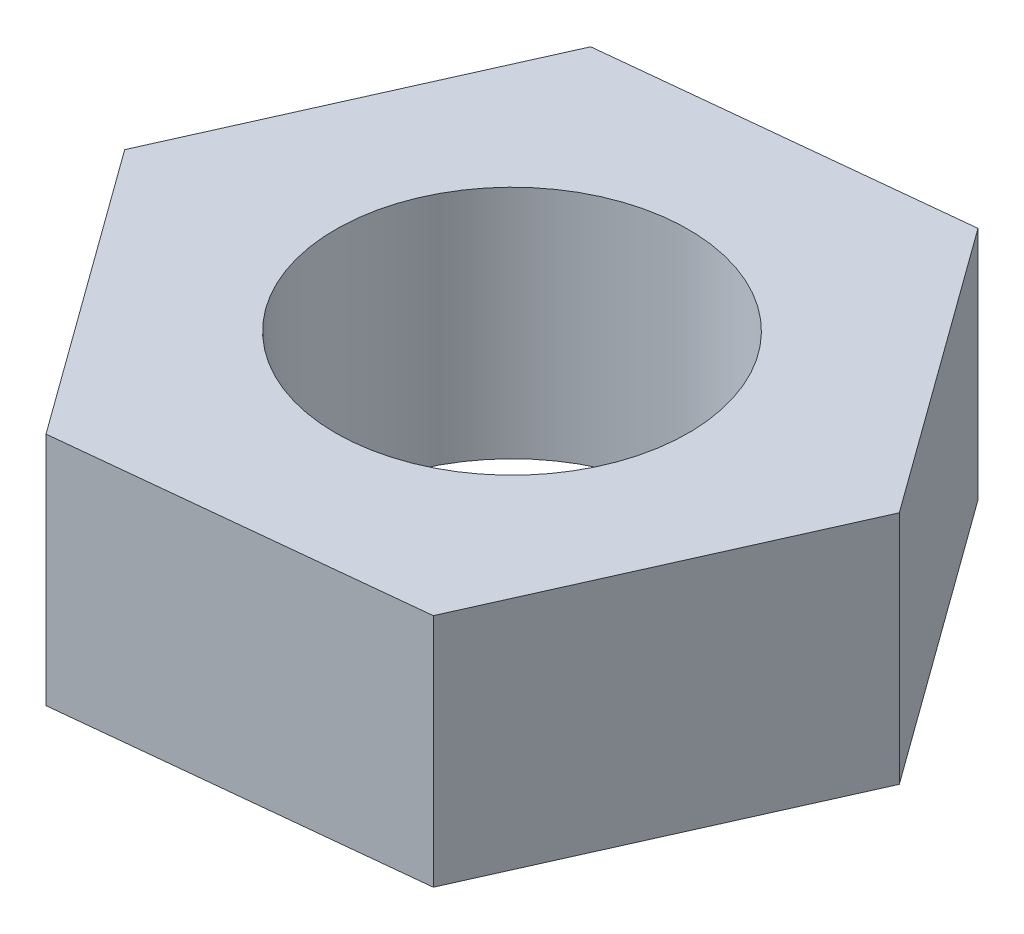
SolidWorks part; units mm, degrees
ref_plane "Plan de face" through (0, 0, 0) normal (0, 0, 1) x (1, 0, 0)
ref_plane "Plan de dessus" through (0, 0, 0) normal (0, 1, 0) x (1, 0, 0)
ref_plane "Plan de droite" through (0, 0, 0) normal (1, 0, 0) x (0, 0, -1)
sketch "Sketch1" plane through (0, 0, 0) normal (0, 1, 0) x (1, 0, 0)
  line L1 (-5.3916, 4.1492) -> (-8.3755, 3.8396)
  line L2 (-8.3755, 3.8396) -> (-9.5994, 1.1005)
  line L3 (-9.5994, 1.1005) -> (-7.8392, -1.3288)
  line L4 (-7.8392, -1.3288) -> (-4.8552, -1.0192)
  line L5 (-4.8552, -1.0192) -> (-3.6314, 1.7198)
  line L6 (-3.6314, 1.7198) -> (-5.3916, 4.1492)
  circle A0 centre (-6.6154, 1.4102) radius 2.5981 construction
  circle A1 centre (-6.6154, 1.4102) radius 1.5
extrude "Boss-Extrude1" add sketch "Sketch1" along normal blind 2
